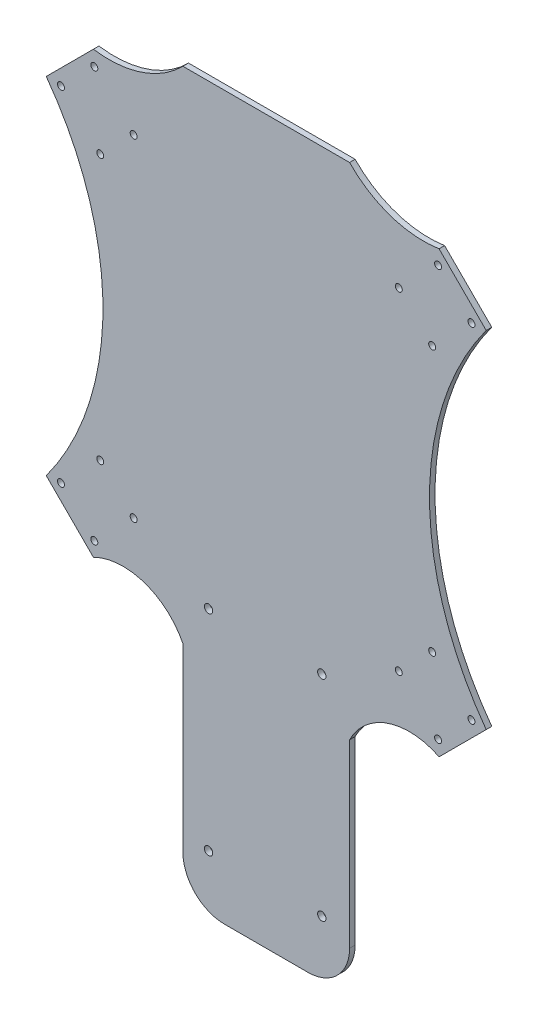
SolidWorks part; units mm, degrees
ref_plane "Front Plane" through (0, 0, 0) normal (0, 0, 1) x (1, 0, 0)
ref_plane "Top Plane" through (0, 0, 0) normal (0, 1, 0) x (1, 0, 0)
ref_plane "Right Plane" through (0, 0, 0) normal (1, 0, 0) x (0, 0, -1)
sketch "Sketch2" plane through (0, 0, 0) normal (0, 0, 1) x (1, 0, 0)
  line L0 (0, 0) -> (0, 50000) construction
  line L1 (0, 0) -> (35355.3391, 35355.3391) construction
  line L2 (0, 0) -> (35355.3391, -35355.3391) construction
  line L3 (-79.196, 62.2254) -> (-62.2254, 79.196)
  line L4 (0, 0) -> (-50000, 0) construction
  line L5 (-79.196, -62.2254) -> (-62.2254, -79.196)
  line L6 (30, 90) -> (-30, 90)
  line L7 (30, -90) -> (30, -155)
  line L8 (79.196, -62.2254) -> (62.2254, -79.196)
  line L9 (-30, -90) -> (-30, -155)
  line L10 (-15, -170) -> (15, -170)
  line L11 (79.196, 62.2254) -> (62.2254, 79.196)
  line L12 (-30, -90) -> (30, -170) construction
  line L13 (-30, -170) -> (30, -90) construction
  arc A0 (-79.196, 62.2254) -> (-79.196, -62.2254) centre (-163.8225, 0) cw
  arc A1 (-62.2254, 79.196) -> (-30, 90) centre (-56.6326, 115.976) ccw
  arc A2 (-62.2254, -79.196) -> (-30, -90) centre (-51.5147, -100.7107) cw
  arc A3 (15, -170) -> (30, -155) centre (15, -155) ccw
  arc A4 (-15, -170) -> (-30, -155) centre (-15, -155) cw
  arc A5 (62.2254, -79.196) -> (30, -90) centre (51.5147, -100.7107) ccw
  arc A6 (79.196, 62.2254) -> (79.196, -62.2254) centre (163.8225, 0) ccw
  arc A7 (62.2254, 79.196) -> (30, 90) centre (56.6326, 115.976) cw
  point P16 (-70.7107, 70.7107)
  point P24 (0, -130)
  point P32 (0, -170)
  point P45 (0, 90)
  dimension "D1" = 170
  dimension "D2" = 45
  dimension "D3" = 45
  dimension "D5" = 30
  dimension "D6" = 60
extrude "Boss-Extrude1" add sketch "Sketch2" along normal blind 2
sketch "Sketch3" plane through (0, 0, 2) normal (0, 0, 1) x (1, 0, 0)
  line L0 (-70.7107, 70.7107) -> (35284.6284, -35284.6284) construction
  line L1 (-79.196, 62.2254) -> (-62.2254, 79.196) construction
  line L2 (0, 90) -> (0, 50090) construction
  line L3 (30, 90) -> (-30, 90) construction
  line L4 (70.7107, 70.7107) -> (35426.0497, 35426.0497) construction
  line L5 (79.196, 62.2254) -> (62.2254, 79.196) construction
  line L6 (0, 0) -> (50000, 0) construction
  circle A0 centre (-73.8927, 61.8718) radius 1.25
  circle A1 centre (-59.7505, 47.7297) radius 1.25
  circle A2 centre (-61.8718, 73.8927) radius 1.25
  circle A3 centre (-47.7297, 59.7505) radius 1.25
  circle A4 centre (59.7505, 47.7297) radius 1.25
  circle A5 centre (73.8927, 61.8718) radius 1.25
  circle A6 centre (61.8718, 73.8927) radius 1.25
  circle A7 centre (47.7297, 59.7505) radius 1.25
  circle A8 centre (-59.7505, -47.7297) radius 1.25
  circle A9 centre (-47.7297, -59.7505) radius 1.25
  circle A10 centre (-61.8718, -73.8927) radius 1.25
  circle A11 centre (-73.8927, -61.8718) radius 1.25
  circle A12 centre (59.7505, -47.7297) radius 1.25
  circle A13 centre (73.8927, -61.8718) radius 1.25
  circle A14 centre (61.8718, -73.8927) radius 1.25
  circle A15 centre (47.7297, -59.7505) radius 1.25
  point P6 (-70.7107, 70.7107)
  point P17 (0, 90)
  point P30 (70.7107, 70.7107)
  dimension "D1" = 8.5
  dimension "D3" = 8.5
  dimension "D2" = 4
  dimension "D4" = 20
extrude "Cut-Extrude1" cut sketch "Sketch3" against normal through all
sketch "Sketch4" plane through (0, 0, 2) normal (0, 0, 1) x (1, 0, 0)
  line L0 (30, -90) -> (30, -155) construction
  line L1 (-20.76, -74.5) -> (20, -74.5)
  line L2 (-20.76, -74.5) -> (-20.76, -150)
  line L3 (-20.76, -150) -> (20, -150)
  line L4 (20, -74.5) -> (20, -150)
  line L5 (-15, -170) -> (15, -170) construction
  circle A0 centre (-20.76, -150) radius 1.5
  circle A1 centre (20, -150) radius 1.5
  circle A2 centre (-20.76, -74.5) radius 1.5
  circle A3 centre (20, -74.5) radius 1.5
  dimension "D1" = 75.5
  dimension "D2" = 40.76
  dimension "D3" = 10
  dimension "D4" = 20
extrude "Cut-Extrude2" cut sketch "Sketch4" against normal through all contours A2 | A3 | A1 | A0
